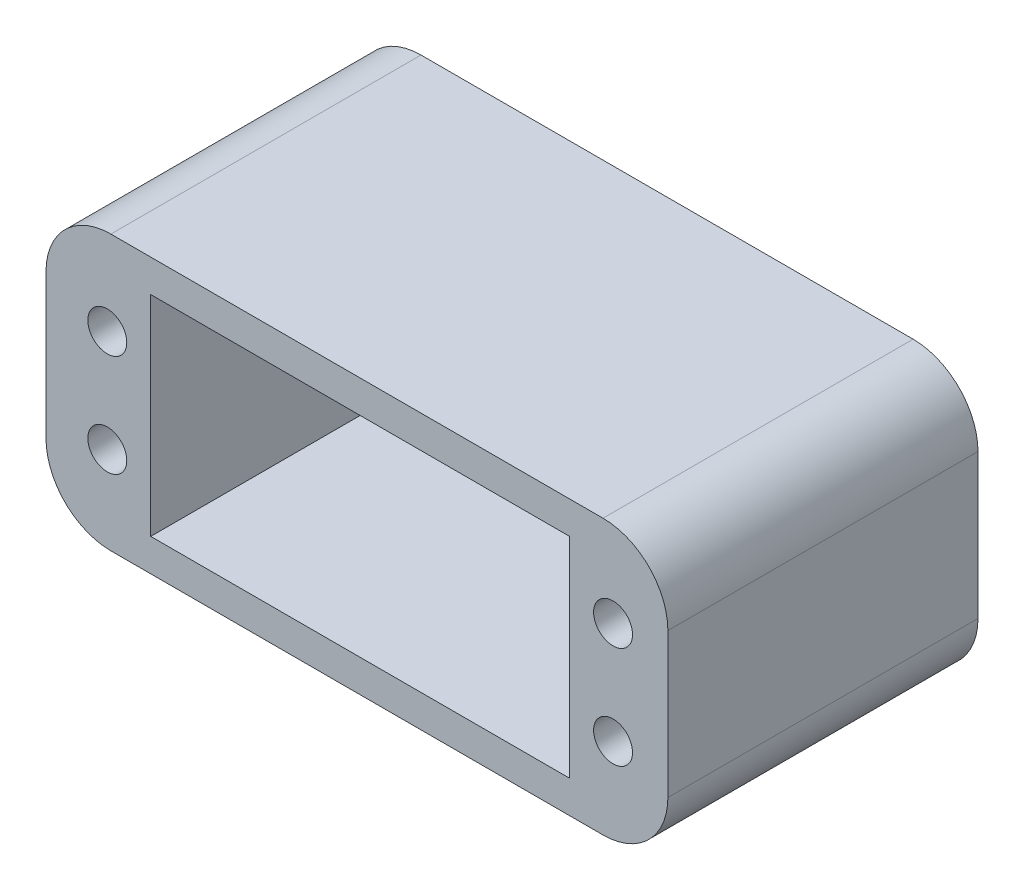
SolidWorks part; units mm, degrees
ref_plane "Front Plane" through (0, 0, 0) normal (0, 0, 1) x (1, 0, 0)
ref_plane "Top Plane" through (0, 0, 0) normal (0, 1, 0) x (1, 0, 0)
ref_plane "Right Plane" through (0, 0, 0) normal (1, 0, 0) x (0, 0, -1)
sketch "Sketch2" plane through (0, 0, 0) normal (0, 0, 1) x (1, 0, 0)
  line L0 (0, 10.25) -> (0, 5) construction
  line L1 (20.5, 10.25) -> (-20.5, 10.25) construction
  line L2 (20.5, 10.25) -> (20.5, -10.25) construction
  line L3 (20.5, -10.25) -> (-20.5, -10.25) construction
  line L4 (-20.5, 10.25) -> (-20.5, -10.25) construction
  line L5 (20.5, 10.25) -> (-20.5, -10.25) construction
  line L6 (20.5, -10.25) -> (-20.5, 10.25) construction
  line L7 (-24.75, 5) -> (24.75, 5) construction
  line L8 (-24.75, 5) -> (-24.75, -5) construction
  line L9 (-24.75, -5) -> (24.75, -5) construction
  line L10 (24.75, 5) -> (24.75, -5) construction
  line L11 (-24.75, 0) -> (-20.5, 0) construction
  line L12 (23.7659, 13.425) -> (-24.4, 13.425)
  line L13 (23.7659, -13.425) -> (-24.4, -13.425)
  line L14 (-30.75, 7.075) -> (-30.75, -7.075)
  line L15 (30.1159, -7.075) -> (30.1159, 7.075)
  circle A0 centre (-24.75, 5) radius 2.5 construction
  circle A1 centre (-24.75, -5) radius 2.5 construction
  circle A2 centre (24.75, 5) radius 2.5 construction
  circle A3 centre (24.75, -5) radius 2.5 construction
  arc A4 (-30.75, -7.075) -> (-24.4, -13.425) centre (-24.4, -7.075) ccw
  arc A5 (-24.4, 13.425) -> (-30.75, 7.075) centre (-24.4, 7.075) ccw
  arc A6 (23.7659, -13.425) -> (30.1159, -7.075) centre (23.7659, -7.075) ccw
  arc A7 (23.7659, 13.425) -> (30.1159, 7.075) centre (23.7659, 7.075) cw
  point P0 (0, 0)
  dimension "D7" = 5
  dimension "D9" = 6.35
  dimension "D1" = 20.5
  dimension "D2" = 41
  dimension "D3" = 49.5
  dimension "D4" = 10
  dimension "D5" = 3.175
  dimension "D6" = 3.175
  dimension "D8" = 6
extrude "Boss-Extrude1" add sketch "Sketch2" along normal mid plane 30.353
sketch "Sketch3" plane through (0, 0, 15.1765) normal (0, 0, 1) x (1, 0, 0)
  line L0 (-20.5, 10.25) -> (-20.5, -10.25)
  line L1 (-20.5, -10.25) -> (20.5, -10.25)
  line L2 (20.5, -10.25) -> (20.5, 10.25)
  line L3 (20.5, 10.25) -> (-20.5, 10.25)
extrude "Cut-Extrude1" cut sketch "Sketch3" against normal offset from surface (27.178 mm away) 3.175 up to face at (-0.3171, 0, -15.1765)
sketch "Sketch4" plane through (0, 0, 15.1765) normal (0, 0, 1) x (1, 0, 0)
  circle A0 centre (-24.75, 5) radius 1.905
  circle A1 centre (-24.75, -5) radius 1.905
  circle A2 centre (24.75, -5) radius 1.905
  circle A3 centre (24.75, 5) radius 1.905
  dimension "D1" = 3.81
extrude "Cut-Extrude2" cut sketch "Sketch4" against normal blind 12.7
sketch "Sketch5" plane through (-30.75, 0, 0) normal (-1, 0, 0) x (0, 0, 1)
  line L0 (-10.3505, -13.425) -> (-10.3505, 13.425) construction
  line L1 (-10.3505, 4.7625) -> (-4.0005, 4.7625)
  line L2 (-10.3505, 4.7625) -> (-10.3505, -4.7625)
  line L3 (-10.3505, -4.7625) -> (-4.0005, -4.7625)
  line L4 (-4.0005, 4.7625) -> (-4.0005, -4.7625)
  line L7 (15.1765, 13.425) -> (-15.1765, 13.425) construction
  line L8 (15.1765, -13.425) -> (-15.1765, -13.425) construction
  line L9 (-15.1765, 7.075) -> (-15.1765, -7.075) construction
  point P4 (0, 0)
  point P9 (-10.3505, 0)
  dimension "D1" = 9.525
  dimension "D2" = 6.35
  dimension "D3" = 4.826
extrude "Cut-Extrude3" cut sketch "Sketch5" against normal up to surface (10.25 mm away) up to face at (-20.5, 0, 1.5875)
